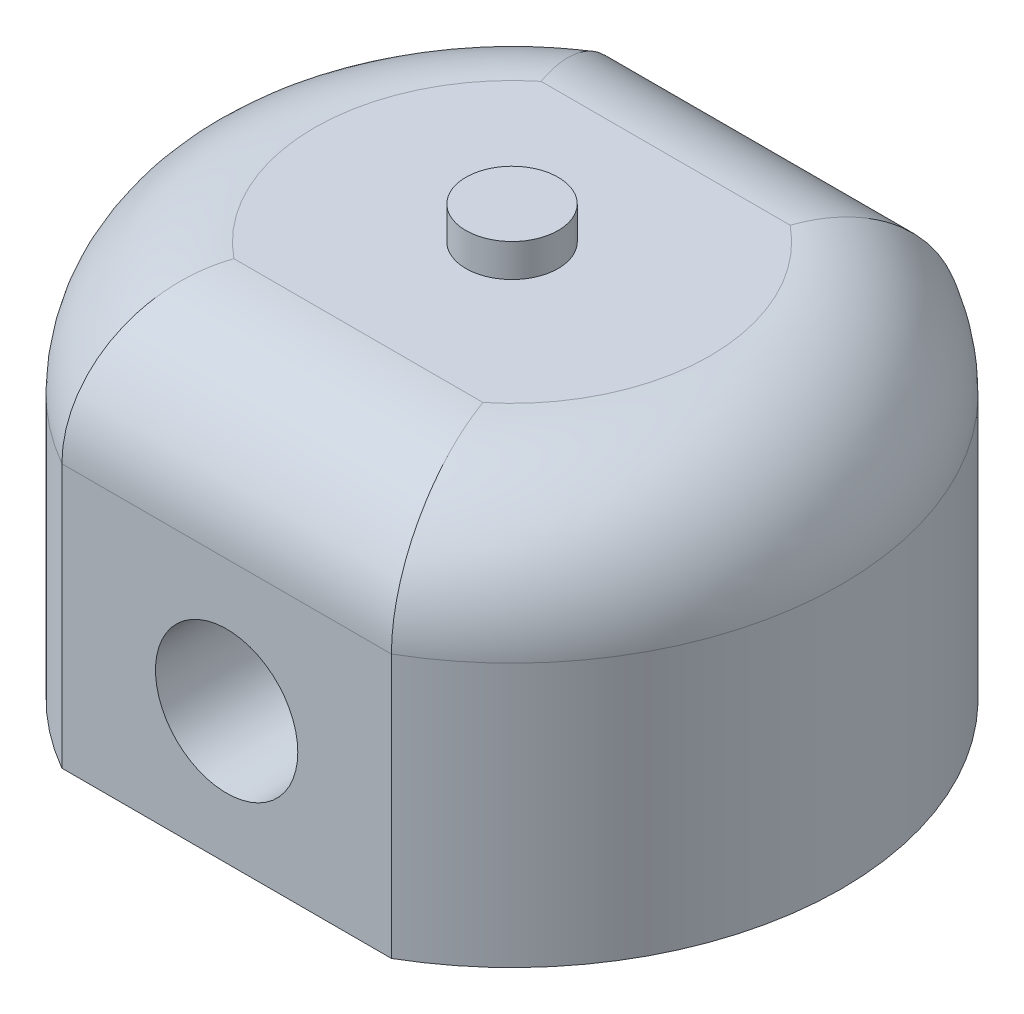
SolidWorks part; units mm, degrees
ref_plane "Front Plane" through (0, 0, 0) normal (0, 0, 1) x (1, 0, 0)
ref_plane "Top Plane" through (0, 0, 0) normal (0, 1, 0) x (1, 0, 0)
ref_plane "Right Plane" through (0, 0, 0) normal (1, 0, 0) x (0, 0, -1)
sketch "Sketch1" plane through (0, 0, 0) normal (0, 1, 0) x (1, 0, 0)
  circle A0 centre (0, 0) radius 31.75
  dimension "D1" = 63.5
extrude "Boss-Extrude1" add sketch "Sketch1" along normal blind 38.1
sketch "Sketch2" plane through (0, 0, 0) normal (0, -1, 0) x (1, 0, 0)
  line L0 (-15.875, 27.4963) -> (15.875, 27.4963)
  line L1 (-15.875, -27.4963) -> (15.875, -27.4963)
  circle A0 centre (0, 0) radius 31.75 construction
  arc A1 (-15.875, -27.4963) -> (15.875, -27.4963) centre (0, 0) ccw
  arc A2 (15.875, 27.4963) -> (-15.875, 27.4963) centre (0, 0) ccw
  dimension "D1" = 31.75
extrude "Cut-Extrude1" cut sketch "Sketch2" against normal through all
fillet "Fillet1" radius 12.7 4 edges at (-31.75, 38.1, 0) (31.75, 38.1, 0) (0, 38.1, 27.4963) (0, 38.1, -27.4963)
hole_wizard "1/4 NPT Tapped Hole1" positions "Sketch5" profile "Sketch4" size "1/4" standard "ANSI Inch"
sketch "Sketch5" plane through (0, 0, 27.4963) normal (0, 0, 1) x (1, 0, 0)
  line L0 (0, 0) -> (0, 25.4) construction
  line L1 (-15.875, 0) -> (15.875, 0) construction
  line L2 (15.875, 25.4) -> (-15.875, 25.4) construction
  point P0 (0, 12.7)
sketch "Sketch4" plane through (0, 12.7, 27.4963) normal (1, 0, 0) x (0, -1, 0)
  line L0 (0, 0) -> (0, 20.3603)
  line L1 (5.5626, 17.018) -> (0, 20.3603)
  line L2 (-5.5626, 17.018) -> (0, 20.3603) construction
  line L3 (5.5626, 17.018) -> (5.5626, 9.906)
  line L4 (5.5626, 9.906) -> (6.558, 9.906)
  line L5 (6.558, 9.906) -> (6.8546, 0)
  line L6 (-6.558, 9.906) -> (-6.8546, 0) construction
  line L7 (6.8546, 0) -> (0, 0)
  line L8 (0, -6.35) -> (0, 107.95) construction
  line L11 (-5.5626, 9.906) -> (-6.558, 9.906) construction
  dimension "Tap Drill Dia." = 11.1252
  dimension "Tap Drill Depth" = 17.018
  dimension "Thread Dia." = 13.7092
  dimension "Thread Angle" = 3.43
  dimension "Thread Depth" = 9.906
  dimension "Drill Angle" = 118
mirror "Mirror1" about plane through (0, 0, 0) normal (0, 0, 1) of "1/4 NPT Tapped Hole1"
hole_wizard "1/4 NPT Tapped Hole2" positions "3DSketch2" profile "Sketch6" size "1/4" standard "ANSI Inch"
sketch3d "3DSketch2"
  line L0 (-26.8587, 0, -16.9314) -> (-26.8587, 25.4, -16.9314) construction
  line L2 (-15.875, 25.4, -27.4963) -> (-15.875, 0, -27.4963) construction
  arc A0 (-15.875, 0, -27.4963) -> (-15.875, 0, 27.4963) centre (0, 0, 0) ccw construction
  arc A1 (-15.875, 25.4, 27.4963) -> (-15.875, 25.4, -27.4963) centre (0, 25.4, 0) ccw construction
  point P0 (-26.8587, 12.7, 16.9314)
  point P2 (-26.8587, 12.7, -16.9314)
  point P12 (0, 31.75, 0)
  point P16 (0, -6.35, 0)
  dimension "D1" = 15.24
sketch "Sketch6" plane through (-26.8587, 12.7, 16.9314) normal (0, 1, 0) x (0.5333, 0, 0.8459)
  line L0 (0, 0) -> (0, 20.3603)
  line L1 (5.5626, 17.018) -> (0, 20.3603)
  line L2 (-5.5626, 17.018) -> (0, 20.3603) construction
  line L3 (5.5626, 17.018) -> (5.5626, 9.906)
  line L4 (5.5626, 9.906) -> (6.558, 9.906)
  line L5 (6.558, 9.906) -> (6.8546, 0)
  line L6 (-6.558, 9.906) -> (-6.8546, 0) construction
  line L7 (6.8546, 0) -> (0, 0)
  line L8 (0, -6.35) -> (0, 107.95) construction
  line L11 (-5.5626, 9.906) -> (-6.558, 9.906) construction
  dimension "Tap Drill Dia." = 11.1252
  dimension "Tap Drill Depth" = 17.018
  dimension "Thread Dia." = 13.7092
  dimension "Thread Angle" = 3.43
  dimension "Thread Depth" = 9.906
  dimension "Drill Angle" = 118
sketch "Sketch7" plane through (0, 0, -27.4963) normal (0, 0, -1) x (-1, 0, 0)
  circle A0 centre (0, 12.7) radius 5.5626
  circle A1 centre (0, 12.7) radius 5.5626 construction
extrude "Cut-Extrude2" cut sketch "Sketch7" against normal through all
sketch "Sketch8" plane through (0, 38.1, 0) normal (0, 1, 0) x (1, 0, 0)
  circle A0 centre (0, 0) radius 4.445
  dimension "D1" = 8.89
extrude "Boss-Extrude2" add sketch "Sketch8" along normal blind 3.175
